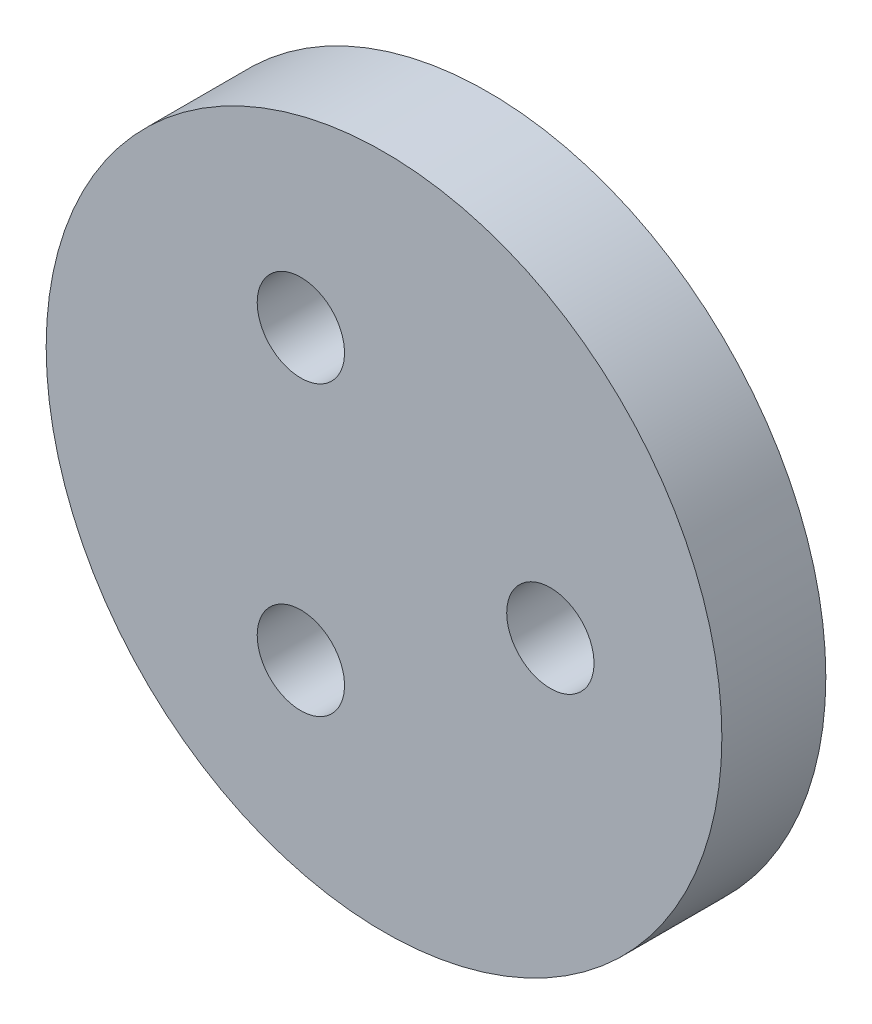
SolidWorks part; units mm, degrees
ref_plane "Front Plane" through (0, 0, 0) normal (0, 0, 1) x (1, 0, 0)
ref_plane "Top Plane" through (0, 0, 0) normal (0, 1, 0) x (1, 0, 0)
ref_plane "Right Plane" through (0, 0, 0) normal (1, 0, 0) x (0, 0, -1)
ref_plane "Plane1" through (0, 0, 10) normal (0, 0, 1) x (1, 0, 0)
sketch "Sketch1" plane through (0, 0, 10) normal (0, 0, 1) x (1, 0, 0)
  circle A0 centre (-8, 13.8564) radius 4.2
  circle A1 centre (-8, -13.8564) radius 4.2
  circle A2 centre (16, 0) radius 4.2
  circle A3 centre (0, 0) radius 32.5
extrude "Boss-Extrude1" add sketch "Sketch1" against normal blind 10
